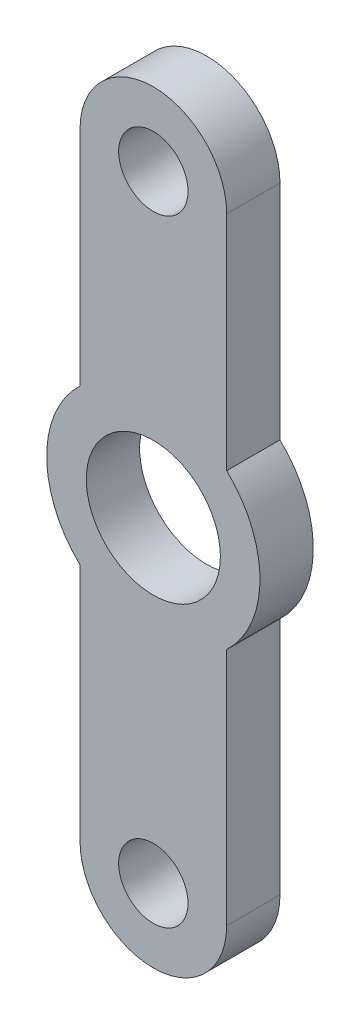
SolidWorks part; units mm, degrees
ref_plane "前视基准面" through (0, 0, 0) normal (0, 0, 1) x (1, 0, 0)
ref_plane "上视基准面" through (0, 0, 0) normal (0, 1, 0) x (1, 0, 0)
ref_plane "右视基准面" through (0, 0, 0) normal (1, 0, 0) x (0, 0, -1)
sketch "草图1" plane through (0, 0, 0) normal (0, 0, 1) x (1, 0, 0)
  line L6 (5.5, 22.5) -> (5.5, 5.8095)
  line L7 (5.5, -23.75) -> (5.5, -5.8095)
  line L8 (0, 0) -> (0, -2.2376) construction
  line L9 (-5.5, -23.75) -> (-5.5, -5.8095)
  line L10 (-5.5, 22.5) -> (-5.5, 5.8095)
  circle A0 centre (0, 0) radius 22.5 construction
  circle A1 centre (0, 0) radius 23.75 construction
  circle A2 centre (0, 22.5) radius 2.6
  circle A3 centre (0, -23.75) radius 2.6
  circle A4 centre (0, 0) radius 5.03
  circle A5 centre (0, 22.5) radius 5.5 construction
  circle A7 centre (0, -23.75) radius 5.5 construction
  arc A8 (-5.5, 22.5) -> (5.5, 22.5) centre (0, 22.5) cw
  arc A9 (-5.5, -23.75) -> (5.5, -23.75) centre (0, -23.75) ccw
  circle A12 centre (0, 0) radius 8 construction
  arc A13 (-5.5, -5.8095) -> (-5.5, 5.8095) centre (0, 0) cw
  arc A14 (5.5, 5.8095) -> (5.5, -5.8095) centre (0, 0) cw
  dimension "D1" = 5.2
  dimension "D2" = 45
  dimension "D3" = 47.5
  dimension "D4" = 10.06
extrude "凸台-拉伸1" add sketch "草图1" along normal blind 4
